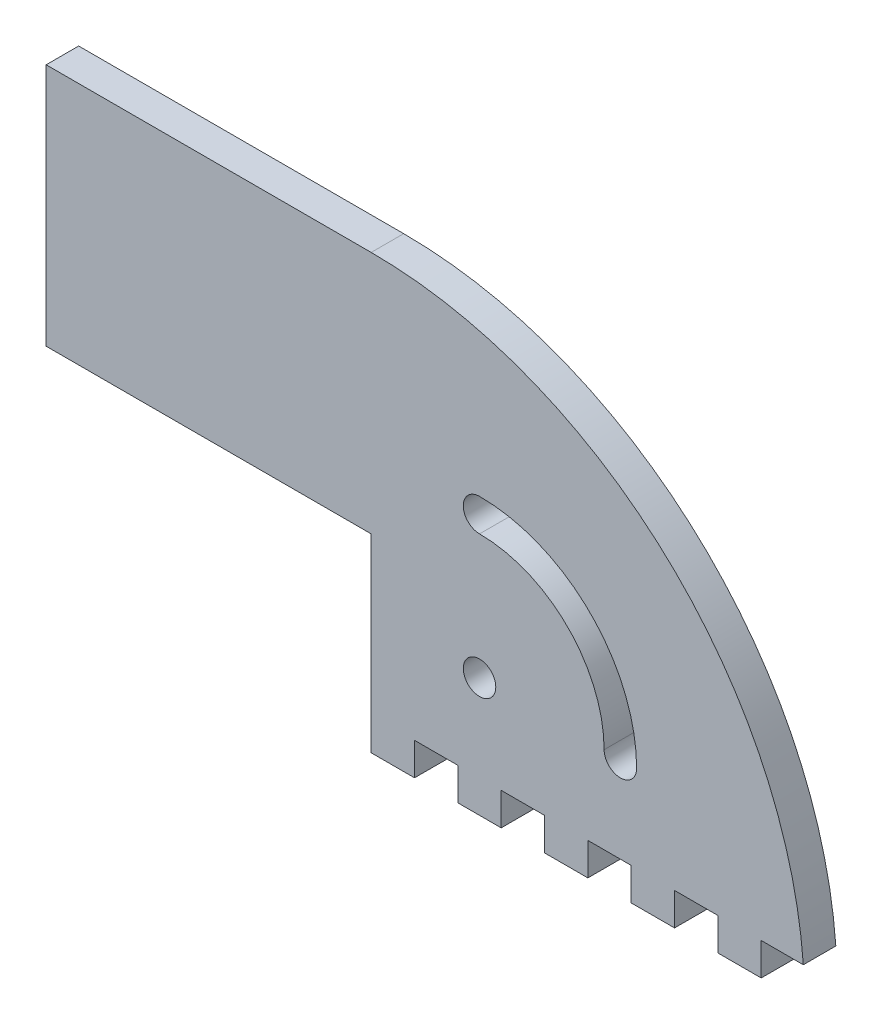
SolidWorks part; units mm, degrees
ref_plane "Plan de face" through (0, 0, 0) normal (0, 0, 1) x (1, 0, 0)
ref_plane "Plan de dessus" through (0, 0, 0) normal (0, 1, 0) x (1, 0, 0)
ref_plane "Plan de droite" through (0, 0, 0) normal (1, 0, 0) x (0, 0, -1)
sketch "Esquisse1" plane through (0, 0, 0) normal (0, 0, 1) x (1, 0, 0)
  line L0 (0, 17.5) -> (0, 0)
  line L1 (0, 0) -> (40, 0)
  line L3 (0, 40) -> (-30, 40)
  line L5 (0, 17.5) -> (-30, 17.5)
  line L6 (-30, 40) -> (-30, 17.5)
  arc A0 (0, 40) -> (40, 0) centre (0, 0) cw
  circle A1 centre (10, 11) radius 1.5
  arc A4 (10, 22.5) -> (10, 25.5) centre (10, 24) cw
  arc A5 (21.5, 11) -> (24.5, 11) centre (23, 11) ccw
  arc A6 (21.5, 11) -> (10, 22.5) centre (10, 11) ccw
  arc A7 (24.5, 11) -> (10, 25.5) centre (10, 11) ccw
  dimension "D3" = 11
  dimension "D4" = 10
  dimension "D5" = 1.5
  dimension "D6" = 1.5
  dimension "D7" = 10
  dimension "D8" = 3
  dimension "D9" = 3
  dimension "D12" = 40
  dimension "D1" = 40
  dimension "D2" = 40
  dimension "D10" = 30
  dimension "D11" = 17.5
  dimension "D13" = 30
extrude "Boss.-Extru.1" add sketch "Esquisse1" along normal blind 3
sketch "Esquisse2" plane through (0, 0, 3) normal (0, 0, 1) x (1, 0, 0)
  line L0 (0, 0) -> (40, 0) construction
  line L1 (4, 0) -> (8, 0)
  line L2 (4, 0) -> (4, 3)
  line L3 (4, 3) -> (8, 3)
  line L4 (8, 0) -> (8, 3)
  line L5 (0, 17.5) -> (0, 0) construction
  dimension "D1" = 4
  dimension "D2" = 3
  dimension "D3" = 4
extrude "Enlèv. mat.-Extru.2" cut sketch "Esquisse2" against normal blind 3
pattern_linear "Répétition linéaire1" count 5 spacing 8 along (1, 0, 0) of "Enlèv. mat.-Extru.2"
